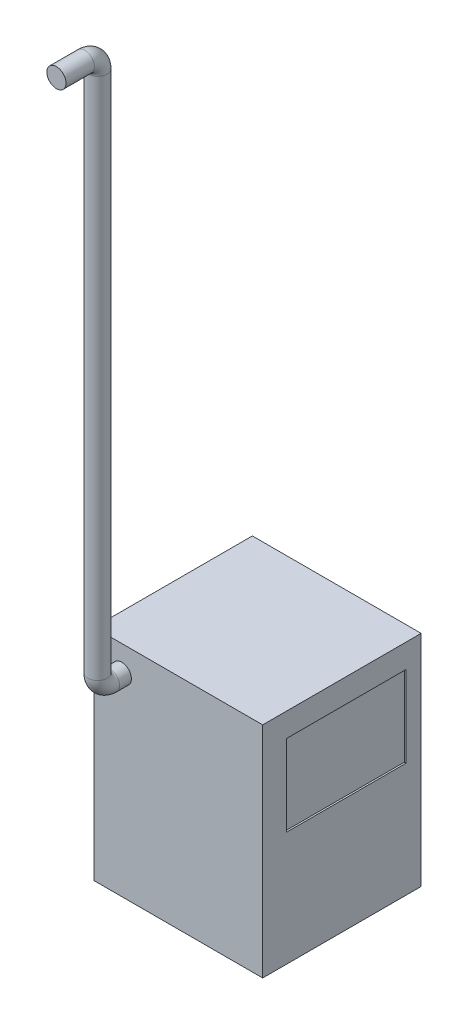
SolidWorks part; units mm, degrees
ref_plane "Front Plane" through (0, 0, 0) normal (0, 0, 1) x (1, 0, 0)
ref_plane "Top Plane" through (0, 0, 0) normal (0, 1, 0) x (1, 0, 0)
ref_plane "Right Plane" through (0, 0, 0) normal (1, 0, 0) x (0, 0, -1)
sketch "Sketch1" plane through (0, 0, 0) normal (1, 0, 0) x (0, 0, -1)
  line L1 (-93.8982, 129.8913) -> (93.8982, 129.8913)
  line L2 (-93.8982, 129.8913) -> (-93.8982, -129.8913)
  line L3 (-93.8982, -129.8913) -> (93.8982, -129.8913)
  line L4 (93.8982, 129.8913) -> (93.8982, -129.8913)
  line L5 (-93.8982, 129.8913) -> (93.8982, -129.8913) construction
  line L6 (-93.8982, -129.8913) -> (93.8982, 129.8913) construction
  point P0 (0, 0)
extrude "Boss-Extrude1" add sketch "Sketch1" along normal blind 200
sketch "Sketch2" plane through (200, 0, 0) normal (1, 0, 0) x (0, 0, -1)
  line L1 (-65.5681, 101.7666) -> (76.1471, 101.7666)
  line L2 (-65.5681, 101.7666) -> (-65.5681, 5.6229)
  line L3 (-65.5681, 5.6229) -> (76.1471, 5.6229)
  line L4 (76.1471, 101.7666) -> (76.1471, 5.6229)
extrude "Cut-Extrude1" cut sketch "Sketch2" against normal blind 2
sketch "Sketch3" plane through (0, 0, 93.8982) normal (0, 0, 1) x (1, 0, 0)
  circle A0 centre (33.0406, 99.3361) radius 11.3679
sketch3d "3DSketch2"
  line L0 (33.0406, 99.3361, 93.8982) -> (33.0406, 99.3361, 107.7727)
  line L1 (33.0406, 114.3361, 122.7727) -> (33.0406, 734.3361, 122.7727)
  line L2 (33.0406, 749.3361, 137.7727) -> (33.0406, 749.3361, 171.3554)
  arc A0 (33.0406, 734.3361, 122.7727) -> (33.0406, 749.3361, 137.7727) centre (33.0406, 734.3361, 137.7727) ccw
  arc A1 (33.0406, 114.3361, 122.7727) -> (33.0406, 99.3361, 107.7727) centre (33.0406, 114.3361, 107.7727) ccw
  point P6 (33.0406, 749.3361, 122.7727)
  point P7 (48.0406, 734.3361, 137.7727)
  point P10 (33.0406, 99.3361, 122.7727)
  point P11 (48.0406, 114.3361, 107.7727)
  dimension "D1" = 15
  dimension "D2" = 650
sweep "Sweep3" add profiles "Sketch3" path "3DSketch2"
